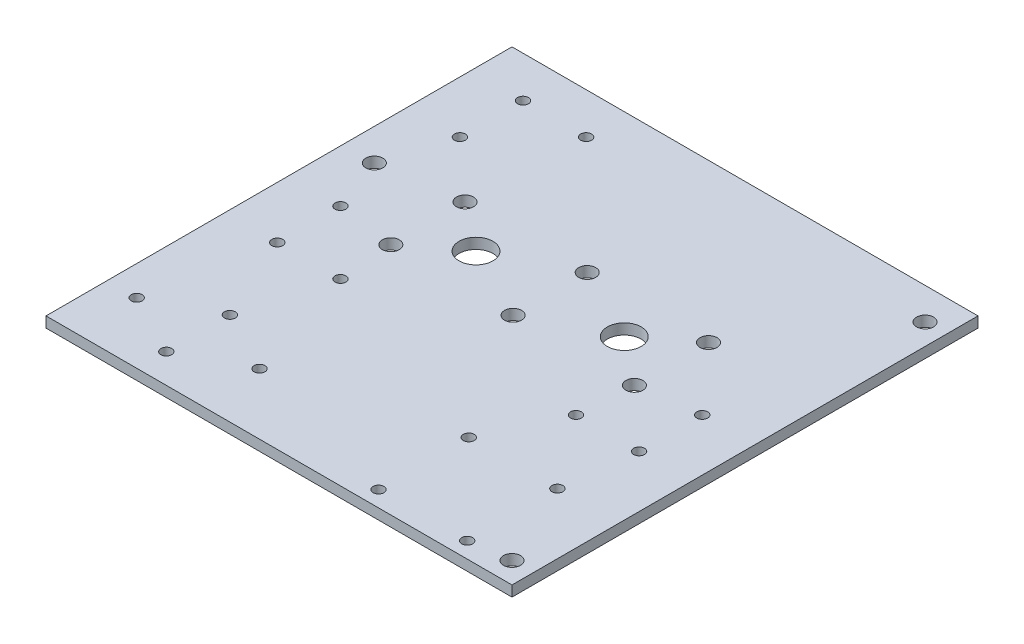
SolidWorks part; units mm, degrees
material "6061 Alloy"
ref_plane "Front Plane" through (0, 0, 0) normal (0, 0, 1) x (1, 0, 0)
ref_plane "Top Plane" through (0, 0, 0) normal (0, 1, 0) x (1, 0, 0)
ref_plane "Right Plane" through (0, 0, 0) normal (1, 0, 0) x (0, 0, -1)
sketch "Sketch1" plane through (0, 0, 0) normal (0, 1, 0) x (1, 0, 0)
  line L1 (-69.85, -69.85) -> (69.85, -69.85)
  line L2 (-69.85, -69.85) -> (-69.85, 69.85)
  line L3 (-69.85, 69.85) -> (69.85, 69.85)
  line L4 (69.85, -69.85) -> (69.85, 69.85)
  line L5 (-69.85, -69.85) -> (69.85, 69.85) construction
  line L6 (-69.85, 69.85) -> (69.85, -69.85) construction
  point P0 (0, 0)
  dimension "D1" = 139.7
  dimension "D2" = 139.7
extrude "Plate" add sketch "Sketch1" along normal blind 3.175 contours L1 L4 L3 L2
sketch "Sketch2" plane through (0, 3.175, 0) normal (0, 1, 0) x (1, 0, 0)
  line L2 (-69.85, 69.85) -> (69.85, 69.85) construction
  line L4 (-69.85, -69.85) -> (-69.85, 69.85) construction
  circle A0 centre (-22.225, 11.43) radius 5.08
  circle A1 centre (22.225, 11.43) radius 5.08
  dimension "D1" = 10.16
  dimension "D2" = 10.16
  dimension "D3" = 47.625
  dimension "D4" = 58.42
  dimension "D5" = 92.075
extrude "Force Sensor Post Holes" cut sketch "Sketch2" against normal through all
hole_wizard "Guidance Screw Holes (#10 clearance)" positions "Sketch6" profile "Sketch5" hole size "#10" standard "ANSI Inch" end condition up to next
sketch "Sketch6" plane through (0, 3.175, 0) normal (0, 1, 0) x (1, 0, 0)
  line L0 (-69.85, 69.85) -> (69.85, 69.85) construction
  line L1 (-69.85, -69.85) -> (-69.85, 69.85) construction
  line L2 (69.85, -69.85) -> (69.85, 69.85) construction
  line L3 (-69.85, -69.85) -> (69.85, -69.85) construction
  point P0 (63.5, -63.5)
  point P2 (-60.325, 19.05)
  point P4 (63.5, 60.325)
  dimension "D1" = 50.8
  dimension "D2" = 9.525
  dimension "D3" = 6.35
  dimension "D4" = 9.525
  dimension "D5" = 6.35
  dimension "D6" = 6.35
sketch "Sketch5" plane through (63.5, 3.175, 63.5) normal (1, 0, 0) x (0, 0, 1)
  line L0 (0, 0) -> (0, 3.175)
  line L1 (0, 3.175) -> (2.5527, 3.175)
  line L2 (2.5527, 3.175) -> (2.5527, 0)
  line L5 (2.5527, 0) -> (0, 0)
  line L11 (0, -6.35) -> (0, 107.95) construction
  dimension "Thru Hole Dia." = 5.1054
  dimension "Thru Hole Depth" = 3.175
sketch "Sketch7" plane through (0, 3.175, 0) normal (0, 1, 0) x (1, 0, 0)
  line L0 (-69.85, -69.85) -> (69.85, -69.85) construction
  line L1 (-69.85, -69.85) -> (-69.85, 69.85) construction
  circle A0 centre (-60.96, -51.562) radius 1.6319
  circle A1 centre (-42.545, -61.087) radius 1.6319
  circle A2 centre (-24.13, -51.562) radius 1.6319
  circle A3 centre (-42.545, -42.037) radius 1.6319
  dimension "D1" = 3.2639
  dimension "D4" = 3.2639
  dimension "D7" = 3.2639
  dimension "D9" = 3.2639
  dimension "D11" = 18.288
  dimension "D12" = 27.305
  dimension "D2" = 18.288
  dimension "D3" = 8.89
  dimension "D5" = 8.763
  dimension "D6" = 27.305
  dimension "D8" = 36.83
  dimension "D10" = 19.05
hole_wizard "Gearbox Mount Holes (#4 clearance)" positions "Sketch9" profile "Sketch8" hole size "#4" standard "ANSI Inch"
sketch "Sketch9" plane through (0, 3.175, 0) normal (0, 1, 0) x (1, 0, 0)
  point P0 (-60.96, -51.562)
  point P3 (-42.545, -42.037)
  point P6 (-24.13, -51.562)
  point P9 (-42.545, -61.087)
sketch "Sketch8" plane through (-60.96, 3.175, 51.562) normal (1, 0, 0) x (0, 0, 1)
  line L0 (0, 0) -> (0, 8.6006)
  line L1 (0, 8.6006) -> (1.6319, 7.62)
  line L2 (1.6319, 7.62) -> (1.6319, 0)
  line L5 (1.6319, 0) -> (0, 0)
  line L10 (0, 8.6006) -> (-1.632, 7.62) construction
  line L11 (0, -6.35) -> (0, 107.95) construction
  dimension "Hole Dia." = 3.2639
  dimension "Hole Depth" = 7.62
  dimension "Drill Angle" = 118
sketch "Sketch10" plane through (0, 3.175, 0) normal (0, 1, 0) x (1, 0, 0)
  line L0 (69.85, -69.85) -> (69.85, 69.85) construction
  line L1 (-69.85, -69.85) -> (69.85, -69.85) construction
  circle A0 centre (51.6509, -65.0875) radius 1.6319
  circle A1 centre (51.6509, -38.0365) radius 1.6319
  circle A2 centre (25.0825, -65.0875) radius 1.6319
  circle A3 centre (25.0825, -38.0365) radius 1.6319
  dimension "D1" = 3.2639
  dimension "D4" = 3.2639
  dimension "D6" = 3.2639
  dimension "D8" = 3.2639
  dimension "D9" = 27.051
  dimension "D10" = 26.5684
  dimension "D11" = 18.1991
  dimension "D12" = 4.7625
  dimension "D2" = 18.1991
  dimension "D3" = 4.7625
  dimension "D5" = 27.051
  dimension "D7" = 26.5684
hole_wizard "Bearing Mount Holes (#4 clearance)" positions "Sketch12" profile "Sketch11" hole size "#4" standard "ANSI Inch"
sketch "Sketch12" plane through (0, 3.175, 0) normal (0, 1, 0) x (1, 0, 0)
  point P0 (25.0825, -38.0365)
  point P3 (51.6509, -38.0365)
  point P6 (25.0825, -65.0875)
  point P9 (51.6509, -65.0875)
sketch "Sketch11" plane through (25.0825, 3.175, 38.0365) normal (1, 0, 0) x (0, 0, 1)
  line L0 (0, 0) -> (0, 8.6006)
  line L1 (0, 8.6006) -> (1.6319, 7.62)
  line L2 (1.6319, 7.62) -> (1.6319, 0)
  line L5 (1.6319, 0) -> (0, 0)
  line L10 (0, 8.6006) -> (-1.632, 7.62) construction
  line L11 (0, -6.35) -> (0, 107.95) construction
  dimension "Hole Dia." = 3.2639
  dimension "Hole Depth" = 7.62
  dimension "Drill Angle" = 118
sketch "Sketch13" plane through (0, 3.175, 0) normal (0, 1, 0) x (1, 0, 0)
  line L1 (-69.85, 69.85) -> (69.85, 69.85) construction
  line L3 (69.85, -69.85) -> (69.85, 69.85) construction
  circle A0 centre (36.3855, 0.3175) radius 2.5527
  circle A2 centre (-36.6395, 0.3175) radius 2.5527
  circle A3 centre (36.3855, 22.5425) radius 2.5527
  circle A5 centre (-36.6395, 22.5425) radius 2.5527
  point P7 (0, 0.3175)
  point P13 (0, 22.5425)
  dimension "D1" = 5.1054
  dimension "D4" = 73.025
  dimension "D7" = 5.1054
  dimension "D8" = 5.1054
  dimension "D10" = 33.4645
  dimension "D11" = 5.1054
  dimension "D2" = 73.025
  dimension "D5" = 22.225
  dimension "D6" = 22.225
  dimension "D9" = 33.4645
  dimension "D12" = 69.5325
  dimension "D3" = 69.5325
hole_wizard "Force Sensor Foundation Holes (#10 clearance)" positions "Sketch17" profile "Sketch16" hole size "#10" standard "ANSI Inch"
sketch "Sketch17" plane through (0, 3.175, 0) normal (0, 1, 0) x (1, 0, 0)
  point P0 (-36.6395, 22.5425)
  point P6 (36.3855, 22.5425)
  point P9 (36.3855, 0.3175)
  point P14 (-36.6395, 0.3175)
  point P17 (0, 0.3175)
  point P20 (0, 22.5425)
sketch "Sketch16" plane through (-36.6395, 3.175, -22.5425) normal (1, 0, 0) x (0, 0, 1)
  line L0 (0, 0) -> (0, 9.1538)
  line L1 (0, 9.1538) -> (2.5527, 7.62)
  line L2 (2.5527, 7.62) -> (2.5527, 0)
  line L5 (2.5527, 0) -> (0, 0)
  line L10 (0, 9.1538) -> (-2.5527, 7.62) construction
  line L11 (0, -6.35) -> (0, 107.95) construction
  dimension "Hole Dia." = 5.1054
  dimension "Hole Depth" = 7.62
  dimension "Drill Angle" = 118
sketch "Sketch18" plane through (0, 3.175, 0) normal (0, 1, 0) x (1, 0, 0)
  line L0 (-54.229, 38.608) -> (-54.229, 57.531) construction
  line L1 (-54.229, 57.531) -> (-35.306, 57.531) construction
  line L2 (-69.85, -69.85) -> (-69.85, 69.85) construction
  line L3 (-69.85, 69.85) -> (69.85, 69.85) construction
  dimension "D1" = 18.923
  dimension "D2" = 18.923
  dimension "D3" = 15.621
  dimension "D4" = 12.319
sketch "Sketch21" plane through (0, 3.175, 0) normal (0, 1, 0) x (1, 0, 0)
  line L0 (-54.229, 2.794) -> (-54.229, -16.129) construction
  line L1 (-54.229, -16.129) -> (-35.306, -16.129) construction
  line L2 (-69.85, -69.85) -> (69.85, -69.85) construction
  line L3 (0, 0) -> (0, 34.4055) construction
  line L4 (54.229, -16.129) -> (35.306, -16.129) construction
  line L5 (54.229, 2.794) -> (54.229, -16.129) construction
  line L6 (69.85, -69.85) -> (69.85, 69.85) construction
  dimension "D1" = 18.923
  dimension "D2" = 18.923
  dimension "D3" = 53.721
  dimension "D4" = 15.621
hole_wizard "Ball Caster Mount Holes (#4 clearance)" positions "Sketch20" profile "Sketch19" hole size "#4" standard "ANSI Inch"
sketch "Sketch20" plane through (0, 3.175, 0) normal (0, 1, 0) x (1, 0, 0)
  point P0 (-35.306, 57.531)
  point P3 (-54.229, 57.531)
  point P6 (-54.229, 38.608)
  point P10 (-54.229, 2.794)
  point P13 (-54.229, -16.129)
  point P16 (-35.306, -16.129)
  point P20 (35.306, -16.129)
  point P23 (54.229, -16.129)
  point P26 (54.229, 2.794)
sketch "Sketch19" plane through (-35.306, 3.175, -57.531) normal (1, 0, 0) x (0, 0, 1)
  line L0 (0, 0) -> (0, 8.6006)
  line L1 (0, 8.6006) -> (1.6319, 7.62)
  line L2 (1.6319, 7.62) -> (1.6319, 0)
  line L5 (1.6319, 0) -> (0, 0)
  line L10 (0, 8.6006) -> (-1.632, 7.62) construction
  line L11 (0, -6.35) -> (0, 107.95) construction
  dimension "Hole Dia." = 3.2639
  dimension "Hole Depth" = 7.62
  dimension "Drill Angle" = 118
